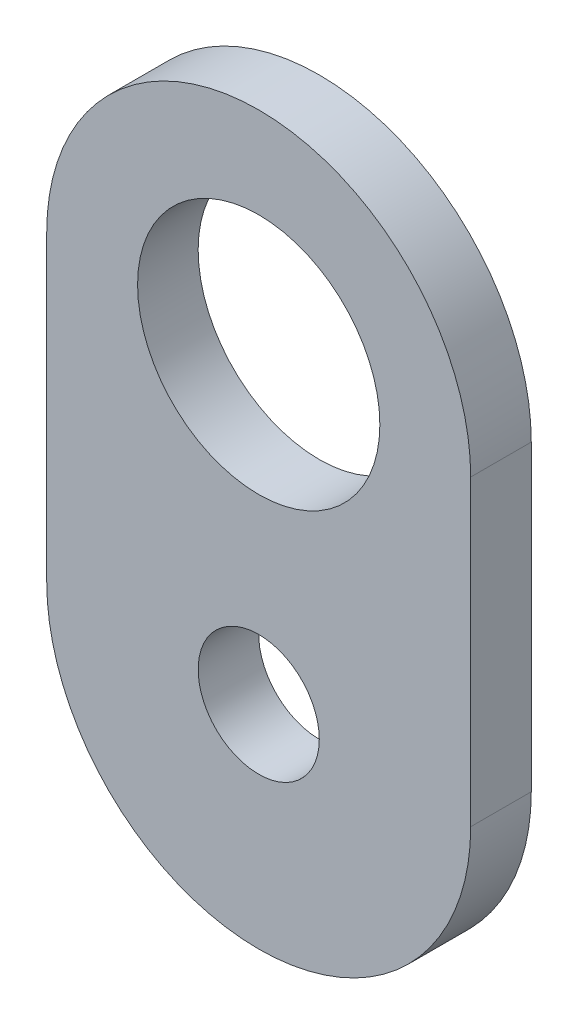
SolidWorks part; units mm, degrees
material "6061-T6 (SS)"
ref_plane "Front Plane" through (0, 0, 0) normal (0, 0, 1) x (1, 0, 0)
ref_plane "Top Plane" through (0, 0, 0) normal (0, 1, 0) x (1, 0, 0)
ref_plane "Right Plane" through (0, 0, 0) normal (1, 0, 0) x (0, 0, -1)
sketch "Sketch1" plane through (0, 0, 0) normal (0, 0, 1) x (1, 0, 0)
  line L0 (0, 0) -> (0, 250.7724) construction
  line L1 (0, 206.7316) -> (0, 270.2316) construction
  line L2 (-44.45, 206.7316) -> (-44.45, 270.2316)
  line L3 (44.45, 206.7316) -> (44.45, 270.2316)
  circle A0 centre (0, 270.2316) radius 25.4
  circle A1 centre (0, 206.7316) radius 12.7
  arc A2 (-44.45, 206.7316) -> (44.45, 206.7316) centre (0, 206.7316) ccw
  arc A3 (44.45, 270.2316) -> (-44.45, 270.2316) centre (0, 270.2316) ccw
  point P7 (0, 238.4816)
  dimension "D1" = 50.8
  dimension "D2" = 25.4
  dimension "D3" = 63.5
  dimension "D4" = 44.45
extrude "Boss-Extrude1" add sketch "Sketch1" along normal blind 12.7
